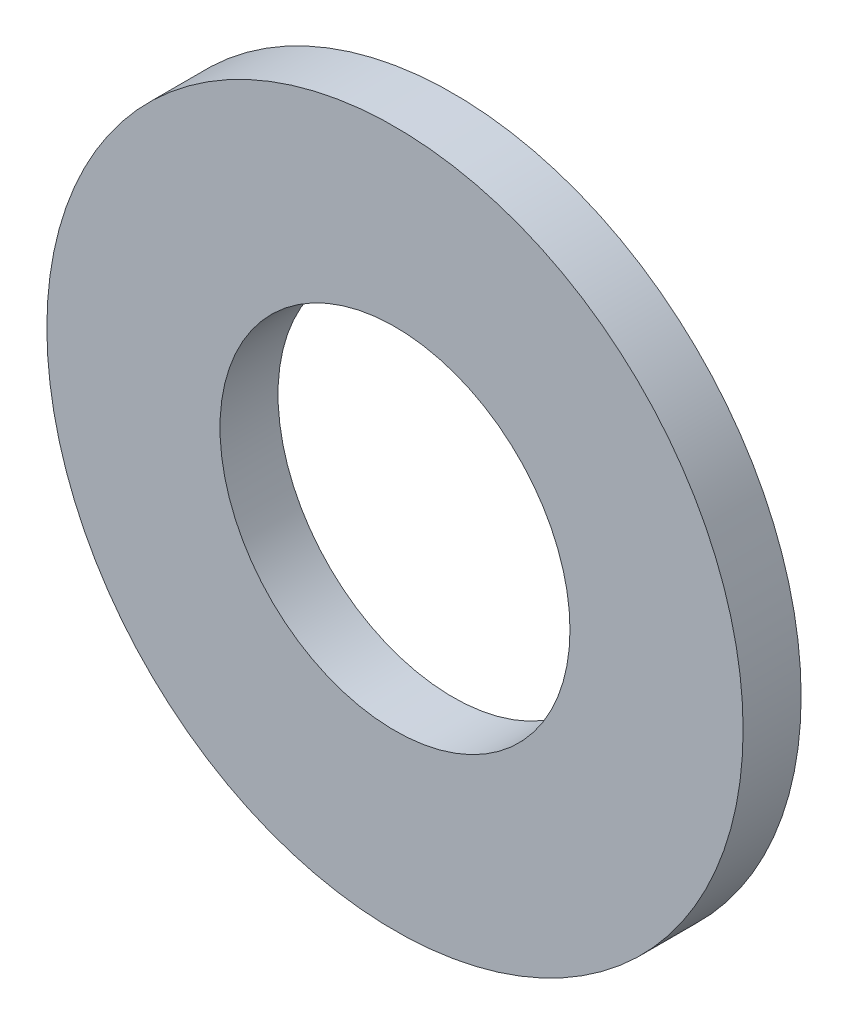
SolidWorks part; units mm, degrees
ref_plane "Front Plane" through (0, 0, 0) normal (0, 0, 1) x (1, 0, 0)
ref_plane "Top Plane" through (0, 0, 0) normal (0, 1, 0) x (1, 0, 0)
ref_plane "Right Plane" through (0, 0, 0) normal (1, 0, 0) x (0, 0, -1)
sketch "Sketch1" plane through (0, 0, 0) normal (0, 0, 1) x (1, 0, 0)
  circle A0 centre (0, 0) radius 9.525
  circle A1 centre (0, 0) radius 4.7879
  dimension "D1" = 19.05
  dimension "ID" = 9.5758
extrude "Extrude1" add sketch "Sketch1" along normal mid plane 1.5875
sketch "Sketch2" plane through (0, 0, 0) normal (1, 0, 0) x (0, 0, -1)
  line L0 (-0.7937, -4.7879) -> (0.7937, -4.7879) construction
  line L3 (0.7937, 4.7879) -> (-0.7937, 4.7879) construction
  line L5 (-0.7937, -4.7879) -> (0.7937, -4.7879)
  line L6 (0.7937, 4.7879) -> (-0.7937, 4.7879)
sketch "Sketch4" plane through (0, 0, 0.7937) normal (0, 0, 1) x (1, 0, 0)
  line L0 (0, 0) -> (-3.3856, 3.3856)
  line L1 (0, -0.8731) -> (0, 0.8731) construction
  circle A0 centre (0, 0) radius 4.7879 construction
  dimension "D1" = 45
